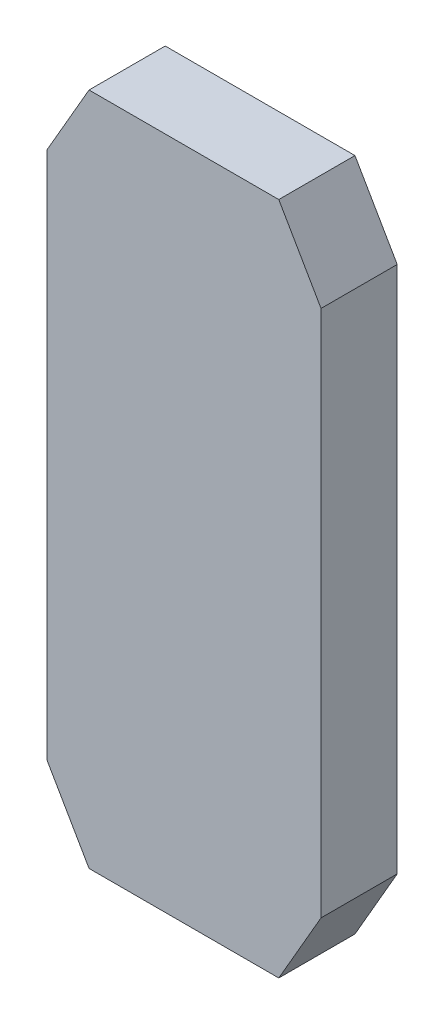
SolidWorks part; units mm, degrees
ref_plane "Front Plane" through (0, 0, 0) normal (0, 0, 1) x (1, 0, 0)
ref_plane "Top Plane" through (0, 0, 0) normal (0, 1, 0) x (1, 0, 0)
ref_plane "Right Plane" through (0, 0, 0) normal (1, 0, 0) x (0, 0, -1)
sketch "Sketch1" plane through (0, 0, 0) normal (0, 0, 1) x (1, 0, 0)
  line L16 (6.2265, -22.1244) -> (9, -17.3205)
  line L17 (-6.2265, -22.1244) -> (6.2265, -22.1244)
  line L18 (-9, -17.3205) -> (-6.2265, -22.1244)
  line L19 (-9, 17.3205) -> (-9, -17.3205)
  line L20 (-6.2265, 22.1244) -> (-9, 17.3205)
  line L21 (6.2265, 22.1244) -> (-6.2265, 22.1244)
  line L22 (9, 17.3205) -> (6.2265, 22.1244)
  line L23 (9, -17.3205) -> (9, 17.3205)
  line L24 (6.2265, -22.1244) -> (9, -17.3205)
  line L25 (-6.2265, -22.1244) -> (6.2265, -22.1244)
  line L26 (-9, -17.3205) -> (-6.2265, -22.1244)
  line L27 (-9, 17.3205) -> (-9, -17.3205)
  line L28 (-6.2265, 22.1244) -> (-9, 17.3205)
  line L29 (6.2265, 22.1244) -> (-6.2265, 22.1244)
  line L30 (9, 17.3205) -> (6.2265, 22.1244)
  line L31 (9, -17.3205) -> (9, 17.3205)
  dimension "D1" = 0.5
extrude "Boss-Extrude1" add sketch "Sketch1" against normal blind 5
shell "Shell1" thickness 1.5
